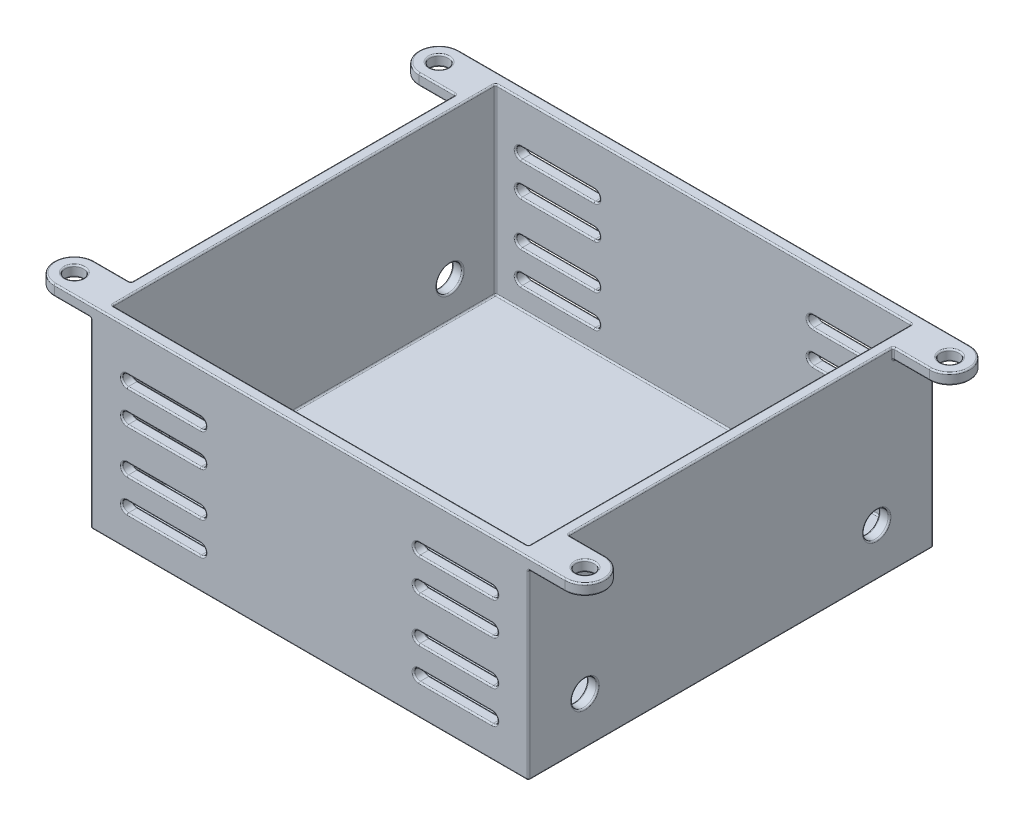
SolidWorks part; units mm, degrees
ref_plane "Front Plane" through (0, 0, 0) normal (0, 0, 1) x (1, 0, 0)
ref_plane "Top Plane" through (0, 0, 0) normal (0, 1, 0) x (1, 0, 0)
ref_plane "Right Plane" through (0, 0, 0) normal (1, 0, 0) x (0, 0, -1)
sketch "Sketch1" plane through (0, 0, 0) normal (0, 1, 0) x (1, 0, 0)
  line L0 (-35, 27.75) -> (35, 27.75) construction
  line L1 (-35, 25) -> (35, 25) construction
  line L2 (-35, 25) -> (-35, -25) construction
  line L3 (-35, -25) -> (35, -25) construction
  line L4 (35, 25) -> (35, -25) construction
  line L5 (-35, 25) -> (35, -25) construction
  line L6 (-35, -25) -> (35, 25) construction
  line L7 (-35, -27.75) -> (35, -27.75) construction
  line L8 (-35, 0) -> (35, 0) construction
  line L9 (0, 25) -> (0, -25) construction
  line L10 (-30, 27.75) -> (-30, -27.75)
  line L11 (-30, -27.75) -> (30, -27.75)
  line L12 (30, -27.75) -> (30, 27.75)
  line L13 (30, 27.75) -> (-30, 27.75)
  line L14 (-35, 22.25) -> (-30, 22.25)
  line L15 (35, 22.25) -> (30, 22.25)
  line L16 (-35, -22.25) -> (-30, -22.25)
  line L17 (35, -22.25) -> (30, -22.25)
  circle A0 centre (35, 25) radius 1.25
  circle A1 centre (35, -25) radius 1.25
  circle A2 centre (-35, -25) radius 1.25
  circle A3 centre (-35, 25) radius 1.25
  circle A4 centre (-35, 25) radius 2.75
  circle A5 centre (35, 25) radius 2.75
  circle A6 centre (35, -25) radius 2.75
  circle A7 centre (-35, -25) radius 2.75
  point P0 (0, 0)
  point P31 (0, 27.75)
  dimension "D3" = 2.5
  dimension "D1" = 70
  dimension "D2" = 50
  dimension "D5" = 60
  dimension "D4" = 1.5
sketch "Sketch2" plane through (0, 0, 0) normal (0, 1, 0) x (1, 0, 0)
  line L0 (-30, -27.75) -> (30, -27.75) construction
  line L1 (30, -27.75) -> (30, 27.75) construction
  line L2 (30, 27.75) -> (-30, 27.75) construction
  line L3 (-30, 27.75) -> (-30, -27.75) construction
  line L4 (-30, -27.75) -> (30, -27.75)
  line L5 (30, -27.75) -> (30, 27.75)
  line L6 (30, 27.75) -> (-30, 27.75)
  line L7 (-30, 27.75) -> (-30, -27.75)
  line L8 (-28.5, 26.25) -> (-28.5, -26.25)
  line L9 (-28.5, -26.25) -> (28.5, -26.25)
  line L10 (28.5, -26.25) -> (28.5, 26.25)
  line L11 (28.5, 26.25) -> (-28.5, 26.25)
  dimension "D1" = 1.5
extrude "Boss-Extrude3" add sketch "Sketch2" against normal blind 25
sketch "Sketch4" plane through (0, -25, 0) normal (0, -1, 0) x (1, 0, 0)
  line L4 (-30, 27.75) -> (-30, -27.75)
  line L5 (-30, -27.75) -> (30, -27.75)
  line L6 (30, -27.75) -> (30, 27.75)
  line L7 (30, 27.75) -> (-30, 27.75)
  line L8 (-30, 27.75) -> (-30, -27.75)
  line L9 (-30, -27.75) -> (30, -27.75)
  line L10 (30, -27.75) -> (30, 27.75)
  line L11 (30, 27.75) -> (-30, 27.75)
  dimension "D1" = 0
extrude "Boss-Extrude4" add sketch "Sketch4" along normal blind 1.5
sketch "Sketch5" plane through (0, 0, 0) normal (0, 1, 0) x (1, 0, 0)
  line L0 (-35, -22.25) -> (-30, -22.25) construction
  line L1 (35, -22.25) -> (30, -22.25) construction
  line L2 (35, 22.25) -> (30, 22.25) construction
  line L3 (-35, 22.25) -> (-30, 22.25) construction
  line L4 (-30, 27.75) -> (-30, -27.75)
  line L5 (-30, -27.75) -> (30, -27.75)
  line L6 (30, -27.75) -> (30, 27.75)
  line L7 (30, 27.75) -> (-30, 27.75)
  line L8 (-30, 27.75) -> (-30, -27.75)
  line L10 (30, -27.75) -> (30, 27.75)
  line L12 (-35, -22.25) -> (-30, -22.25)
  line L13 (35, -22.25) -> (30, -22.25)
  line L14 (35, 22.25) -> (30, 22.25)
  line L15 (-35, 22.25) -> (-30, 22.25)
  line L16 (-28.5, -26.25) -> (28.5, -26.25) construction
  line L17 (28.5, -26.25) -> (28.5, 26.25) construction
  line L18 (28.5, 26.25) -> (-28.5, 26.25) construction
  line L19 (-28.5, 26.25) -> (-28.5, -26.25) construction
  line L20 (-28.5, -26.25) -> (28.5, -26.25)
  line L21 (28.5, -26.25) -> (28.5, 26.25)
  line L22 (28.5, 26.25) -> (-28.5, 26.25)
  line L23 (-28.5, 26.25) -> (-28.5, -26.25)
  line L24 (-35, 27.75) -> (35, 27.75) construction
  line L25 (-35, 27.75) -> (35, 27.75)
  line L26 (-35, -27.75) -> (35, -27.75) construction
  line L27 (-35, -27.75) -> (35, -27.75)
  circle A0 centre (-35, -25) radius 1.25 construction
  circle A1 centre (-35, -25) radius 2.75 construction
  circle A2 centre (35, -25) radius 1.25 construction
  circle A3 centre (35, -25) radius 2.75 construction
  circle A4 centre (35, 25) radius 1.25 construction
  circle A5 centre (35, 25) radius 2.75 construction
  circle A6 centre (-35, 25) radius 1.25 construction
  circle A7 centre (-35, 25) radius 2.75 construction
  circle A8 centre (-35, -25) radius 1.25
  circle A9 centre (-35, -25) radius 2.75
  circle A10 centre (35, -25) radius 1.25
  circle A11 centre (35, -25) radius 2.75
  circle A12 centre (35, 25) radius 1.25
  circle A13 centre (35, 25) radius 2.75
  circle A14 centre (-35, 25) radius 1.25
  circle A15 centre (-35, 25) radius 2.75
  line M9 (-30, 27.75) -> (-30, -27.75)
  line M11 (30, -27.75) -> (30, 27.75)
  dimension "D1" = 0
extrude "Boss-Extrude5" add sketch "Sketch5" against normal blind 1.5 contours A9 L27 L8 L12 | A11 L13 L27 M11 | A13 L25 L14 M11 | A15 L15 L25 M9 | A8 | A10 | A12 | A14
sketch "Sketch6" plane through (0, 0, 0) normal (0, 0, 1) x (1, 0, 0)
  line L0 (-30, -14) -> (30, -14) construction
  line L1 (-30, -26.5) -> (-30, -1.5) construction
  line L2 (30, -26.5) -> (30, -1.5) construction
  line L3 (-25, -6.5) -> (-15, -6.5) construction
  line L4 (-25, -5.75) -> (-15, -5.75)
  line L5 (-25, -7.25) -> (-15, -7.25)
  line L6 (-25, -11) -> (-15, -11) construction
  line L7 (-25, -10.25) -> (-15, -10.25)
  line L8 (-25, -11.75) -> (-15, -11.75)
  line L9 (0, -14) -> (0, -22.9254) construction
  line L10 (-25, -17) -> (-15, -17) construction
  line L11 (-25, -17.75) -> (-15, -17.75)
  line L12 (-25, -16.25) -> (-15, -16.25)
  line L13 (-25, -21.5) -> (-15, -21.5) construction
  line L14 (-25, -22.25) -> (-15, -22.25)
  line L15 (-25, -20.75) -> (-15, -20.75)
  line L16 (25, -6.5) -> (15, -6.5) construction
  line L17 (25, -5.75) -> (15, -5.75)
  line L18 (25, -7.25) -> (15, -7.25)
  line L19 (25, -11) -> (15, -11) construction
  line L20 (25, -10.25) -> (15, -10.25)
  line L21 (25, -11.75) -> (15, -11.75)
  line L22 (25, -17) -> (15, -17) construction
  line L23 (25, -17.75) -> (15, -17.75)
  line L24 (25, -16.25) -> (15, -16.25)
  line L25 (25, -21.5) -> (15, -21.5) construction
  line L26 (25, -22.25) -> (15, -22.25)
  line L27 (25, -20.75) -> (15, -20.75)
  arc A0 (-25, -5.75) -> (-25, -7.25) centre (-25, -6.5) ccw
  arc A1 (-15, -7.25) -> (-15, -5.75) centre (-15, -6.5) ccw
  arc A2 (-25, -10.25) -> (-25, -11.75) centre (-25, -11) ccw
  arc A3 (-15, -11.75) -> (-15, -10.25) centre (-15, -11) ccw
  arc A4 (-25, -17.75) -> (-25, -16.25) centre (-25, -17) cw
  arc A5 (-15, -16.25) -> (-15, -17.75) centre (-15, -17) cw
  arc A6 (-25, -22.25) -> (-25, -20.75) centre (-25, -21.5) cw
  arc A7 (-15, -20.75) -> (-15, -22.25) centre (-15, -21.5) cw
  arc A8 (25, -5.75) -> (25, -7.25) centre (25, -6.5) cw
  arc A9 (15, -7.25) -> (15, -5.75) centre (15, -6.5) cw
  arc A10 (25, -10.25) -> (25, -11.75) centre (25, -11) cw
  arc A11 (15, -11.75) -> (15, -10.25) centre (15, -11) cw
  arc A12 (25, -17.75) -> (25, -16.25) centre (25, -17) ccw
  arc A13 (15, -16.25) -> (15, -17.75) centre (15, -17) ccw
  arc A14 (25, -22.25) -> (25, -20.75) centre (25, -21.5) ccw
  arc A15 (15, -20.75) -> (15, -22.25) centre (15, -21.5) ccw
  point P8 (-20, -6.5)
  point P16 (-20, -11)
  point P25 (-20, -17)
  point P32 (-20, -21.5)
  point P39 (20, -6.5)
  point P46 (20, -11)
  point P53 (20, -17)
  point P60 (20, -21.5)
  dimension "D1" = 1.5
  dimension "D2" = 10
  dimension "D3" = 7.5
  dimension "D4" = 20
  dimension "D5" = 4.5
extrude "Cut-Extrude1" cut sketch "Sketch6" along normal up to surface and the other way up to surface up to face at (0, -7.375, 27.75) other way up to face at (0, -7.375, -27.75)
sketch "Sketch9" plane through (0, 0, 0) normal (1, 0, 0) x (0, 0, -1)
  line L0 (0, 0) -> (0, -20) construction
  line L1 (0, -20) -> (-20, -20) construction
  circle A0 centre (-20, -20) radius 1.75
  circle A1 centre (20, -20) radius 1.75
  dimension "D3" = 3.5
  dimension "D1" = 20
  dimension "D2" = 20
extrude "Cut-Extrude7" cut sketch "Sketch9" along normal up to surface and the other way up to surface up to face at (30, -7.375, 0) other way up to face at (-30, -7.375, 0)
fillet "Fillet1" radius 0.2 196 edges at (30, -20, -21.75) (-30, -20, -18.25) (-30, -20, 21.75) (30, -20, 18.25) (-28.5, -20, -18.25) (28.5, -20, -21.75) (-28.5, -20, 21.75) (28.5, -20, 18.25) (14.25, -21.5, 27.75) (20, -20.75, 27.75) (25.75, -21.5, 27.75) (20, -22.25, 27.75) (25.75, -21.5, -27.75) (20, -22.25, -27.75) (14.25, -21.5, -27.75) (20, -20.75, -27.75) (14.25, -17, 27.75) (20, -16.25, 27.75) (25.75, -17, 27.75) (20, -17.75, 27.75) (25.75, -17, -27.75) (20, -17.75, -27.75) (14.25, -17, -27.75) (20, -16.25, -27.75) (14.25, -11, 27.75) (20, -10.25, 27.75) (25.75, -11, 27.75) (20, -11.75, 27.75) (25.75, -11, -27.75) (20, -11.75, -27.75) (14.25, -11, -27.75) (20, -10.25, -27.75) (14.25, -6.5, 27.75) (20, -5.75, 27.75) (25.75, -6.5, 27.75) (20, -7.25, 27.75) (25.75, -6.5, -27.75) (20, -7.25, -27.75) (14.25, -6.5, -27.75) (20, -5.75, -27.75) (-14.25, -21.5, 27.75) (-20, -22.25, 27.75) (-25.75, -21.5, 27.75) (-20, -20.75, 27.75) (-25.75, -21.5, -27.75) (-20, -20.75, -27.75) (-14.25, -21.5, -27.75) (-20, -22.25, -27.75) (-14.25, -17, 27.75) (-20, -17.75, 27.75) (-25.75, -17, 27.75) (-20, -16.25, 27.75) (-25.75, -17, -27.75) (-20, -16.25, -27.75) (-14.25, -17, -27.75) (-20, -17.75, -27.75) (-14.25, -11, 27.75) (-20, -11.75, 27.75) (-25.75, -11, 27.75) (-20, -10.25, 27.75) (-25.75, -11, -27.75) (-20, -10.25, -27.75) (-14.25, -11, -27.75) (-20, -11.75, -27.75) (-20, -7.25, -27.75) (-14.25, -6.5, -27.75) (-20, -5.75, -27.75) (-25.75, -6.5, -27.75) (-20, -5.75, 27.75) (-25.75, -6.5, 27.75) (-20, -7.25, 27.75) (-14.25, -6.5, 27.75) (-20, -5.75, -26.25) (-14.25, -6.5, -26.25) (-20, -7.25, -26.25) (-25.75, -6.5, -26.25) (20, -22.25, -26.25) (14.25, -21.5, -26.25) (20, -20.75, -26.25) (25.75, -21.5, -26.25) (20, -17.75, -26.25) (14.25, -17, -26.25) (20, -16.25, -26.25) (25.75, -17, -26.25) (20, -11.75, -26.25) (14.25, -11, -26.25) (20, -10.25, -26.25) (25.75, -11, -26.25) (-20, -10.25, -26.25) (-14.25, -11, -26.25) (-20, -11.75, -26.25) (-25.75, -11, -26.25) (-20, -16.25, -26.25) (-14.25, -17, -26.25) (-20, -17.75, -26.25) (-25.75, -17, -26.25) (-20, -20.75, -26.25) (-14.25, -21.5, -26.25) (-20, -22.25, -26.25) (-25.75, -21.5, -26.25) (20, -7.25, -26.25) (14.25, -6.5, -26.25) (20, -5.75, -26.25) (25.75, -6.5, -26.25) (-30, -0.75, 22.25) (-32.5, 0, 22.25) (-32.5, -1.5, 22.25) (-30, -1.5, 25) (-32.5, -1.5, 27.75) (-37.75, -1.5, 25) (-37.75, 0, 25) (-35, -1.5, 26.25) (-35, 0, 26.25) (30, -0.75, -22.25) (32.5, 0, -22.25) (32.5, -1.5, -22.25) (30, -1.5, -25) (32.5, -1.5, -27.75) (37.75, -1.5, -25) (37.75, 0, -25) (35, -1.5, -23.75) (35, 0, -23.75) (-30, -0.75, -22.25) (-32.5, -1.5, -27.75) (-30, -1.5, -25) (-32.5, 0, -22.25) (-32.5, -1.5, -22.25) (-37.75, -1.5, -25) (-37.75, 0, -25) (-35, -1.5, -23.75) (-35, 0, -23.75) (35, 0, 26.25) (35, -1.5, 26.25) (37.75, -1.5, 25) (37.75, 0, 25) (32.5, 0, 22.25) (32.5, -1.5, 22.25) (30, -1.5, 25) (32.5, -1.5, 27.75) (30, -0.75, 22.25) (0, -26.5, 27.75) (-30, -26.5, 0) (0, -26.5, -27.75) (30, -26.5, 0) (0, 0, -26.25) (-28.5, 0, 0) (0, 0, 26.25) (28.5, 0, 0) (0, -25, -26.25) (-28.5, -25, 0) (0, -25, 26.25) (28.5, -25, 0) (-28.5, -12.5, -26.25) (-28.5, -12.5, 26.25) (28.5, -12.5, 26.25) (28.5, -12.5, -26.25) (-30, 0, 0) (0, 0, 27.75) (30, 0, 0) (0, 0, -27.75) (-30, -14, 27.75) (30, -14, 27.75) (30, -14, -27.75) (-20, -5.75, 26.25) (-14.25, -6.5, 26.25) (-20, -7.25, 26.25) (-25.75, -6.5, 26.25) (20, -22.25, 26.25) (14.25, -21.5, 26.25) (20, -20.75, 26.25) (25.75, -21.5, 26.25) (20, -17.75, 26.25) (14.25, -17, 26.25) (20, -16.25, 26.25) (25.75, -17, 26.25) (20, -11.75, 26.25) (14.25, -11, 26.25) (20, -10.25, 26.25) (25.75, -11, 26.25) (-20, -10.25, 26.25) (-14.25, -11, 26.25) (-20, -11.75, 26.25) (-25.75, -11, 26.25) (-20, -16.25, 26.25) (-14.25, -17, 26.25) (-20, -17.75, 26.25) (-25.75, -17, 26.25) (-20, -20.75, 26.25) (-14.25, -21.5, 26.25) (-20, -22.25, 26.25) (-25.75, -21.5, 26.25) (20, -7.25, 26.25) (14.25, -6.5, 26.25) (20, -5.75, 26.25) (25.75, -6.5, 26.25) (-30, -14, -27.75)
